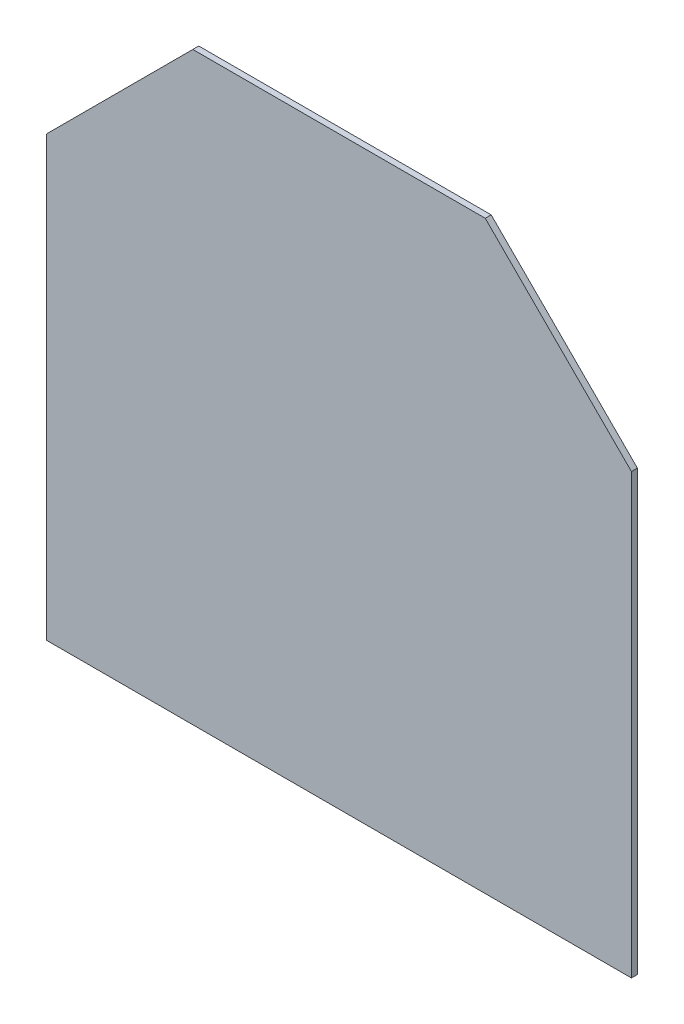
SolidWorks part; units mm, degrees
ref_plane "Front Plane" through (0, 0, 0) normal (1, 0, 0) x (0, 1, 0)
ref_plane "Top Plane" through (0, 0, 0) normal (0, 0, 1) x (0, 1, 0)
ref_plane "Right Plane" through (0, 0, 0) normal (0, 1, 0) x (-1, 0, 0)
sketch "glass" plane through (0, 0, 1.06) normal (0, 0, -1) x (1, 0, 0)
  line L0 (45.0008, -80) -> (15.0008, -80)
  line L1 (15.0008, -80) -> (0.0008, -65)
  line L2 (0.0008, -65) -> (0.0008, -20)
  line L3 (0.0008, -20) -> (60.0008, -20)
  line L4 (60.0008, -20) -> (60.0008, -65)
  line L5 (60.0008, -65) -> (45.0008, -80)
  line L7 (0.0008, -10.3548) -> (0.0008, -28.3548) construction
  line L8 (5, -80) -> (55, -80) construction
  dimension "D1" = 60
  dimension "D2" = 60
  dimension "D3" = 30
  dimension "D4" = 135
extrude "extrude_glass" add sketch "glass" along normal blind 0.61 from surface at 0
equation "\"D1\"= 0.61"
